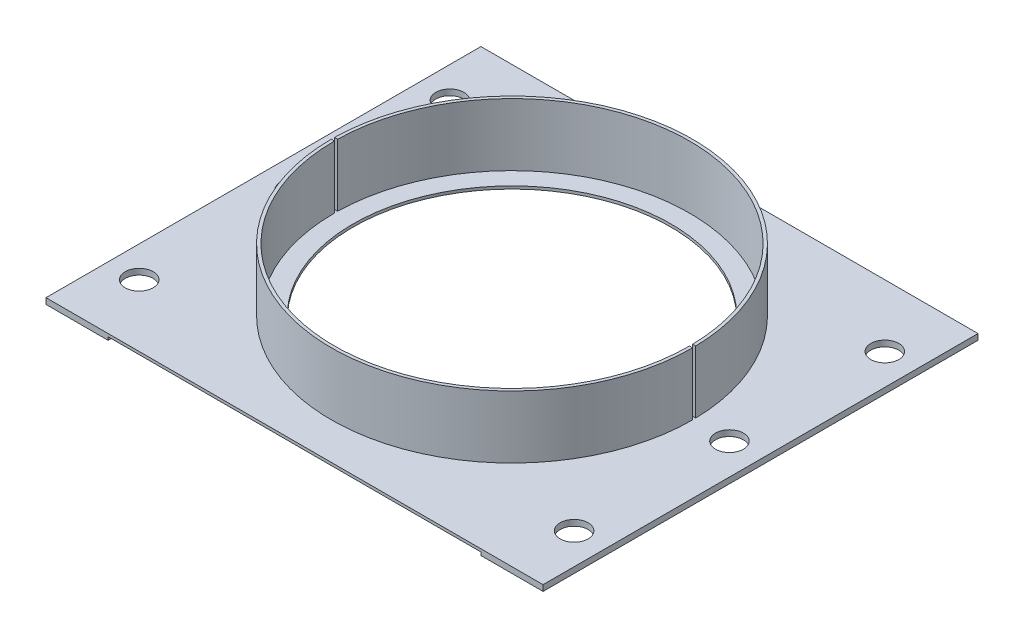
SolidWorks part; units mm, degrees
material "Acero galvanizado"
ref_plane "Alzado" through (0, 0, 0) normal (0, 0, 1) x (1, 0, 0)
ref_plane "Planta" through (0, 0, 0) normal (0, 1, 0) x (1, 0, 0)
ref_plane "Vista lateral" through (0, 0, 0) normal (1, 0, 0) x (0, 0, -1)
sketch "Croquis1" plane through (0, 0, 0) normal (0, 1, 0) x (1, 0, 0)
  line L1 (-80, 70) -> (80, 70)
  line L2 (-80, 70) -> (-80, -70)
  line L3 (-80, -70) -> (80, -70)
  line L4 (80, 70) -> (80, -70)
  line L5 (-80, 70) -> (80, -70) construction
  line L6 (-80, -70) -> (80, 70) construction
  line L11 (-47.7165, 41.7519) -> (58.7139, -51.3747) construction
  circle A0 centre (0, 0) radius 51.15
  point P0 (0, 0)
  point P6 (0, 0)
  point P13 (0, 0)
  point P14 (0, 0)
  point P15 (0, 0)
  dimension "D3" = 102.3
  dimension "D2" = 140
  dimension "D4" = 160
extrude "Saliente-Extruir1" add sketch "Croquis1" along normal blind 0.9
sketch "Croquis4" plane through (0, 0, 0) normal (0, -1, 0) x (1, 0, 0)
  line L0 (-80, 70) -> (80, 70) construction
  line L1 (80, -70) -> (60, -70)
  line L2 (80, -70) -> (80, 70)
  line L3 (80, 70) -> (60, 70)
  line L4 (60, -70) -> (60, 70)
  line L5 (0, -70) -> (0, 70) construction
  line L6 (80, -70) -> (-80, -70) construction
  line L7 (-60, -70) -> (-60, 70)
  line L8 (-80, 70) -> (-60, 70)
  line L9 (-80, -70) -> (-80, 70)
  line L10 (-80, -70) -> (-60, -70)
  dimension "D1" = 20
extrude "Saliente-Extruir3" add sketch "Croquis4" along normal blind 1
hole_wizard "Taladro de margen para M81" positions "Croquis3D2" profile "Croquis2" hole size "M8" standard "Ansi Metric"
sketch3d "Croquis3D2"
  line L8 (-80, 0.9, -70) -> (-80, 0.9, 70) construction
  line L9 (80, 0.9, 70) -> (80, 0.9, -70) construction
  line L10 (-80, 0.9, 70) -> (80, 0.9, 70) construction
  point P0 (-70, 0.9, -50)
  point P2 (-70, 0.9, 0)
  point P4 (-70, 0.9, 50)
  point P6 (70, 0.9, 50)
  point P8 (70, 0.9, 0)
  point P10 (70, 0.9, -50)
  point P48 (0, 0, 0)
  point P49 (-158.7563, 0, -25.4356)
  point P50 (0, 0, 0)
  point P51 (0, 0, 0)
  point P52 (0, 0, 0)
  point P57 (0, 0, 0)
  point P59 (0, 0, 0)
  point P64 (0, 0, 0)
  dimension "D1" = 20
  dimension "D2" = 50
  dimension "D3" = 50
  dimension "D8" = 20
  dimension "D4" = 50
  dimension "D5" = 50
  dimension "D6" = 10
  dimension "D7" = 10
sketch "Croquis2" plane through (-70, 0.9, -50) normal (1, 0, 0) x (0, 0, 1)
  line L0 (0, 0) -> (0, 12.7039)
  line L1 (0, 12.7039) -> (4.5, 10)
  line L2 (4.5, 10) -> (4.5, 0)
  line L5 (4.5, 0) -> (0, 0)
  line L10 (0, 12.7039) -> (-4.5, 10) construction
  line L11 (0, -6.35) -> (0, 107.95) construction
  dimension "Diámetro de taladro" = 9
  dimension "Profundidad de taladro" = 10
  dimension "Ángulo de perforador" = 118
sketch "Croquis5" plane through (0, 0, 0) normal (0, -1, 0) x (1, 0, 0)
  line L0 (57.15, 0) -> (-57.15, 0) construction
  line L2 (-57.15, 0) -> (-58.15, 0)
  line L4 (0, 0) -> (0, -57.15) construction
  line L6 (57.15, 0) -> (58.15, 0)
  line L7 (-57.1413, -1) -> (-58.1414, -1)
  line L8 (57.1413, -1) -> (58.1414, -1)
  line L9 (57.15, 0) -> (58.15, 0)
  arc A2 (-57.1413, -1) -> (57.1413, -1) centre (0, 0) ccw
  arc A3 (-58.1414, -1) -> (58.1414, -1) centre (0, 0) ccw
  circle A4 centre (0, 0) radius 58.15 construction
  circle A5 centre (0, 0) radius 57.15 construction
  arc A6 (58.15, 0) -> (-58.15, 0) centre (0, 0) ccw
  arc A7 (57.15, 0) -> (-57.15, 0) centre (0, 0) ccw
  dimension "D1" = 114.3
  dimension "D2" = 1
  dimension "D3" = 1
extrude "Saliente-Extruir4" add sketch "Croquis5" against normal blind 21 contours A7 L6 A6 L2 | A3 L8 A2 L7
